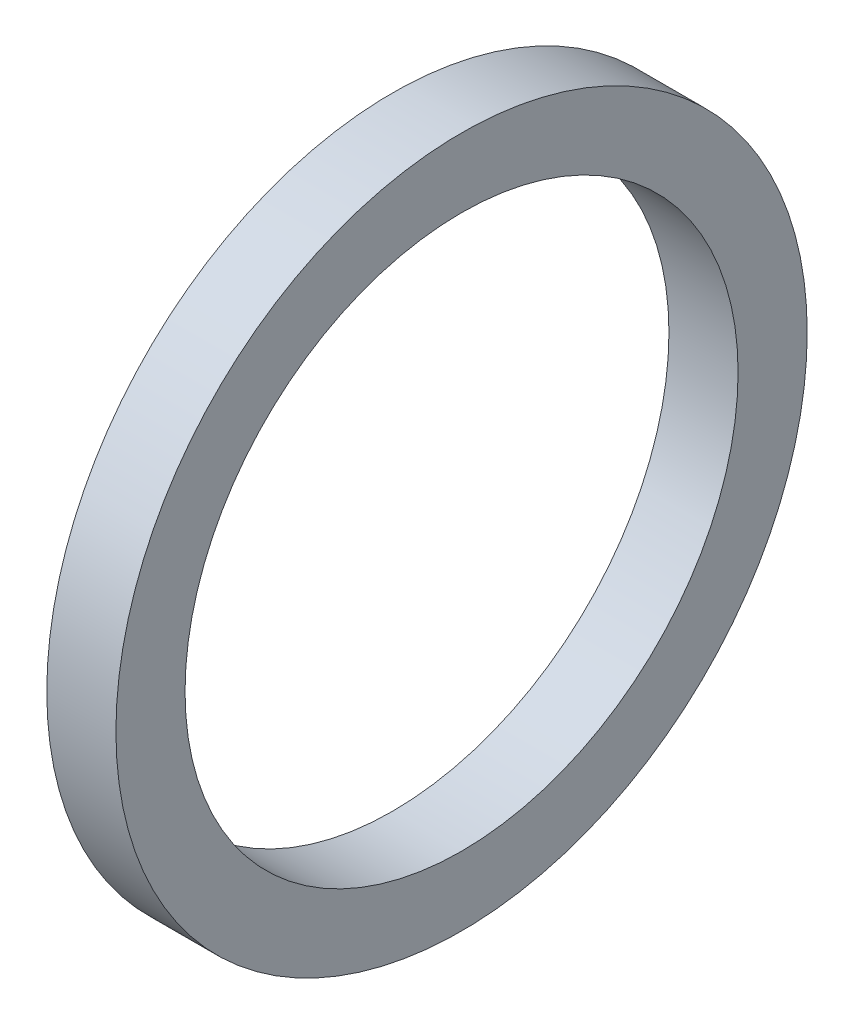
SolidWorks part; units mm, degrees
ref_plane "Спереди" through (0, 0, 0) normal (0, 0, 1) x (1, 0, 0)
ref_plane "Сверху" through (0, 0, 0) normal (0, 1, 0) x (1, 0, 0)
ref_plane "Справа" through (0, 0, 0) normal (1, 0, 0) x (0, 0, -1)
sketch "Эскиз1" plane through (0, 0, 0) normal (1, 0, 0) x (0, 0, -1)
  circle A0 centre (0, 0) radius 5
  circle A1 centre (0, 0) radius 4
  dimension "D1" = 8
  dimension "D2" = 10
extrude "Бобышка-Вытянуть1" add sketch "Эскиз1" along normal blind 1
